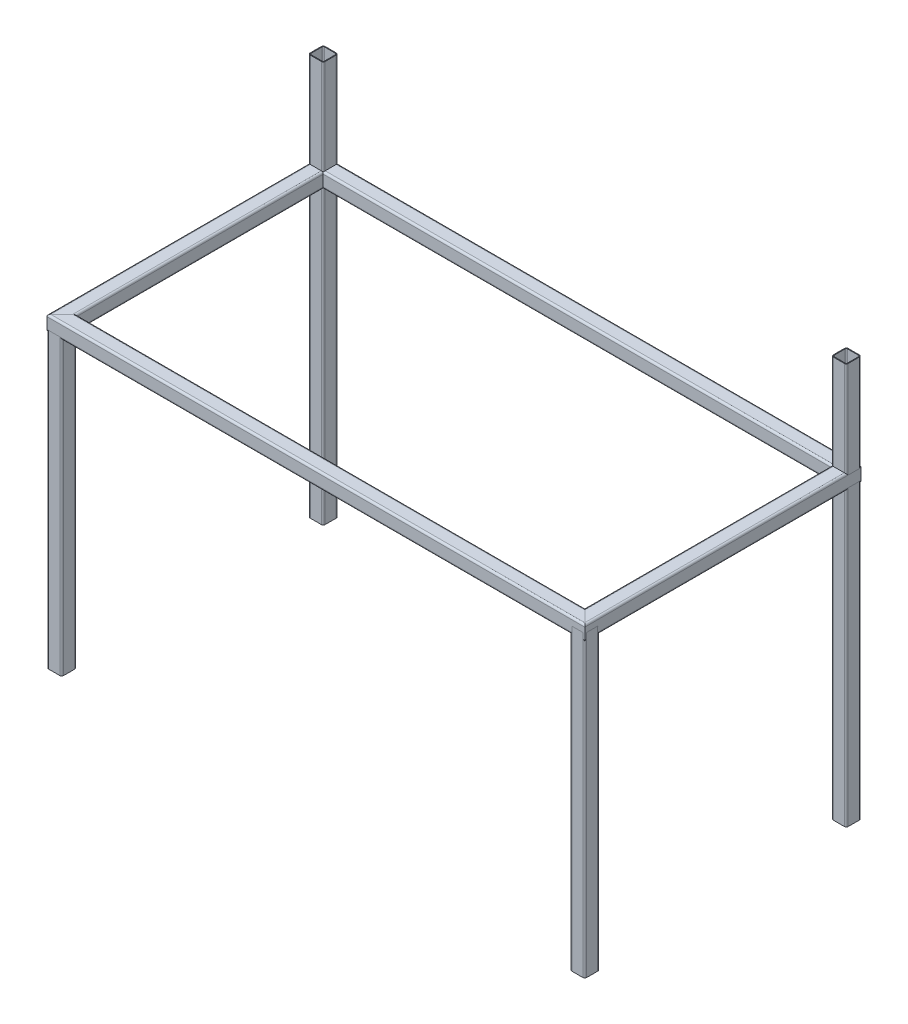
SolidWorks part; units mm, degrees
ref_plane "Front Plane" through (0, 0, 0) normal (0, 0, 1) x (1, 0, 0)
ref_plane "Top Plane" through (0, 0, 0) normal (0, 1, 0) x (1, 0, 0)
ref_plane "Right Plane" through (0, 0, 0) normal (1, 0, 0) x (0, 0, -1)
sketch3d "3DSketch1"
  line L0 (-700, 0, 350) -> (-700, 800, 350)
  line L1 (-700, 800, 350) -> (700, 800, 350)
  line L2 (700, 800, 350) -> (700, 0, 350)
  line L3 (700, 800, 350) -> (700, 800, -350)
  line L4 (700, 800, -350) -> (-700, 800, -350)
  line L5 (-700, 800, -350) -> (-700, 800, 350)
  line L6 (-700, 1073.458, -350) -> (-700, 0, -350)
  line L7 (700, 1073.458, -350) -> (700, 0, -350)
  line L8 (-700, 800, 350) -> (700, 800, -350) construction
  line L9 (-700, 800, -350) -> (700, 800, 350) construction
  line L10 (-700, 150, 350) -> (-700, 150, -350)
  line L11 (-700, 150, -350) -> (700, 150, -350)
  line L12 (700, 150, -350) -> (700, 150, 350)
  point P11 (0, 800, 0)
  dimension "D1" = 800
  dimension "D2" = 1400
  dimension "D3" = 700
  dimension "D4" = 150
other "Rectangular tube - configured 40 X 40 X 2(1)"
ref_plane "Plane1" through (-700, 800, 350) normal (1, 0, 0) x (0, 0, -1)
sketch "Sketch12" plane through (-700, 800, 350) normal (1, 0, 0) x (0, 0, -1)
  line L0 (-14.8, -18) -> (14.8, -18)
  line L1 (-18, -14.8) -> (-18, 14.8)
  line L2 (14.8, 18) -> (-14.8, 18)
  line L3 (18, 14.8) -> (18, -14.8)
  line L4 (-14.8, -20) -> (14.8, -20)
  line L5 (-20, -14.8) -> (-20, 14.8)
  line L6 (14.8, 20) -> (-14.8, 20)
  line L7 (20, 14.8) -> (20, -14.8)
  arc A0 (20, 14.8) -> (14.8, 20) centre (14.8, 14.8) ccw
  arc A1 (14.8, -20) -> (20, -14.8) centre (14.8, -14.8) ccw
  arc A2 (-20, -14.8) -> (-14.8, -20) centre (-14.8, -14.8) ccw
  arc A3 (-14.8, 20) -> (-20, 14.8) centre (-14.8, 14.8) ccw
  arc A4 (-14.8, 18) -> (-18, 14.8) centre (-14.8, 14.8) ccw
  arc A5 (18, 14.8) -> (14.8, 18) centre (14.8, 14.8) ccw
  arc A6 (14.8, -18) -> (18, -14.8) centre (14.8, -14.8) ccw
  arc A7 (-18, -14.8) -> (-14.8, -18) centre (-14.8, -14.8) ccw
  point P0 (0, 20)
  point P1 (20, 0)
  point P2 (0, -20)
  point P3 (-20, 0)
  point P4 (-20, 20)
  point P5 (20, 20)
  point P6 (20, -20)
  point P7 (-20, -20)
  point P8 (0, 0)
  point P33 (0, 0)
  dimension "D1" = 5.2
  dimension "Thickness" = 2
  dimension "V_leg" = 40
  dimension "H_leg" = 40
other "Rectangular tube - configured 40 X 40 X 2(2)"
ref_plane "Plane2" through (-700, 1073.458, -350) normal (0, -1, 0) x (1, 0, 0)
sketch "Sketch1" plane through (-700, 1073.458, -350) normal (0, -1, 0) x (1, 0, 0)
  line L0 (-14.8, -18) -> (14.8, -18)
  line L1 (-18, -14.8) -> (-18, 14.8)
  line L2 (14.8, 18) -> (-14.8, 18)
  line L3 (18, 14.8) -> (18, -14.8)
  line L4 (-14.8, -20) -> (14.8, -20)
  line L5 (-20, -14.8) -> (-20, 14.8)
  line L6 (14.8, 20) -> (-14.8, 20)
  line L7 (20, 14.8) -> (20, -14.8)
  arc A0 (20, 14.8) -> (14.8, 20) centre (14.8, 14.8) ccw
  arc A1 (14.8, -20) -> (20, -14.8) centre (14.8, -14.8) ccw
  arc A2 (-20, -14.8) -> (-14.8, -20) centre (-14.8, -14.8) ccw
  arc A3 (-14.8, 20) -> (-20, 14.8) centre (-14.8, 14.8) ccw
  arc A4 (-14.8, 18) -> (-18, 14.8) centre (-14.8, 14.8) ccw
  arc A5 (18, 14.8) -> (14.8, 18) centre (14.8, 14.8) ccw
  arc A6 (14.8, -18) -> (18, -14.8) centre (14.8, -14.8) ccw
  arc A7 (-18, -14.8) -> (-14.8, -18) centre (-14.8, -14.8) ccw
  point P0 (0, 20)
  point P1 (20, 0)
  point P2 (0, -20)
  point P3 (-20, 0)
  point P4 (-20, 20)
  point P5 (20, 20)
  point P6 (20, -20)
  point P7 (-20, -20)
  point P8 (0, 0)
  point P33 (0, 0)
  dimension "D1" = 5.2
  dimension "Thickness" = 2
  dimension "V_leg" = 40
  dimension "H_leg" = 40
